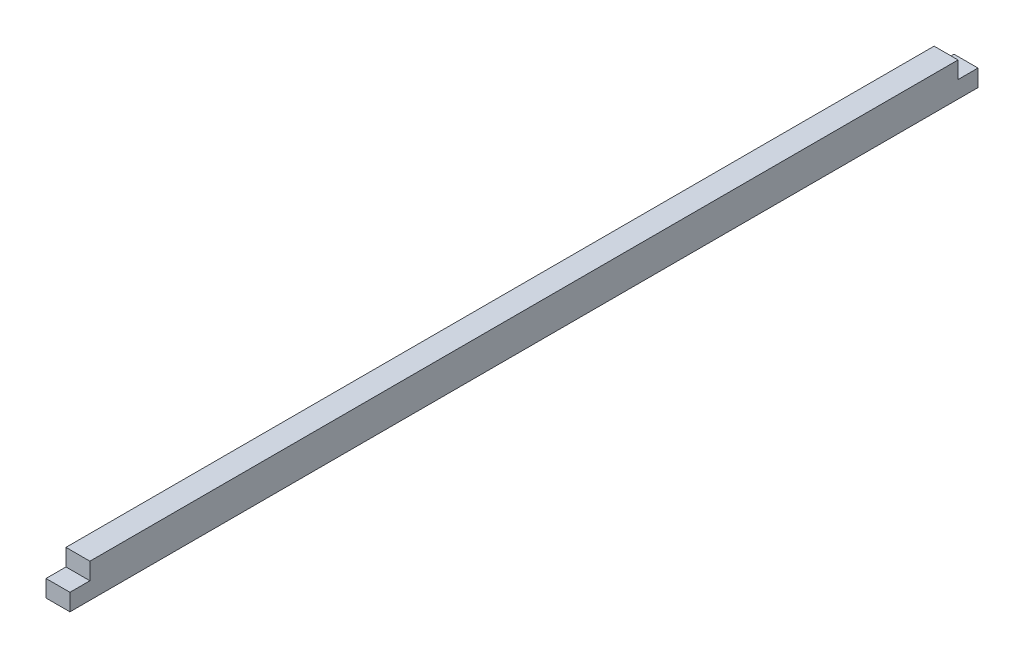
SolidWorks part; units mm, degrees
ref_plane "Front Plane" through (0, 0, 0) normal (0, 0, 1) x (1, 0, 0)
ref_plane "Top Plane" through (0, 0, 0) normal (0, 1, 0) x (1, 0, 0)
ref_plane "Right Plane" through (0, 0, 0) normal (1, 0, 0) x (0, 0, -1)
sketch "Sketch1" plane through (0, 0, 0) normal (1, 0, 0) x (0, 0, -1)
  line L1 (0, 0) -> (455, 0)
  line L2 (0, 0) -> (0, 17)
  line L3 (0, 17) -> (455, 17)
  line L4 (455, 0) -> (455, 17)
  dimension "D1" = 455
  dimension "D2" = 17
extrude "Boss-Extrude1" add sketch "Sketch1" along normal blind 12
sketch "Sketch2" plane through (12, 0, 0) normal (1, 0, 0) x (0, 0, -1)
  line L0 (227.5, 17) -> (227.5, 0) construction
  line L1 (0, 17) -> (10, 17)
  line L2 (0, 17) -> (0, 8.5)
  line L3 (0, 8.5) -> (10, 8.5)
  line L4 (10, 17) -> (10, 8.5)
  line L5 (455, 17) -> (0, 17) construction
  line L6 (0, 0) -> (455, 0) construction
  line L7 (455, 8.5) -> (445, 8.5)
  line L8 (445, 17) -> (445, 8.5)
  line L9 (455, 17) -> (445, 17)
  line L10 (455, 17) -> (455, 8.5)
  dimension "D1" = 8.5
  dimension "D2" = 10
extrude "Cut-Extrude1" cut sketch "Sketch2" against normal blind 12
